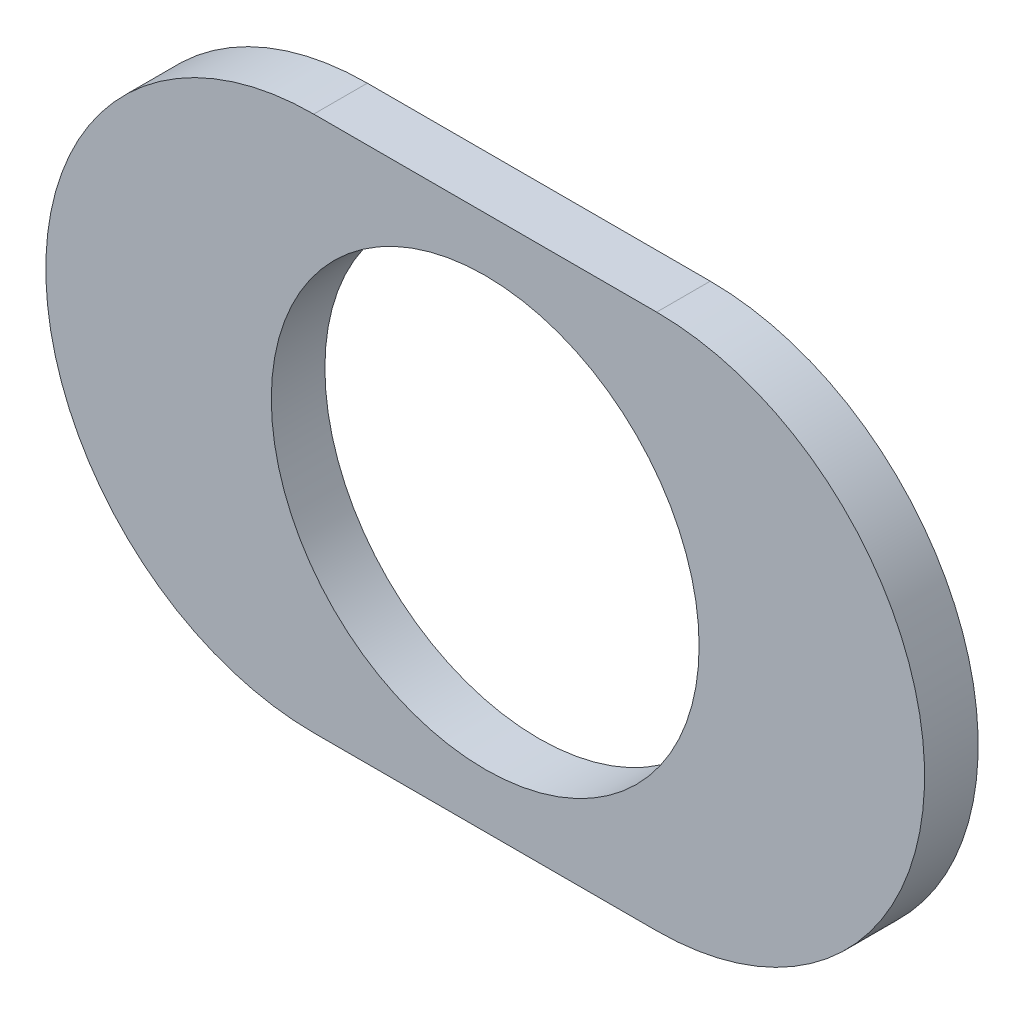
SolidWorks part; units mm, degrees
material "Delrin 2700 NC010, Low Viscosity Acetal Copolymer (SS)"
ref_plane "Front Plane" through (0, 0, 0) normal (0, 0, 1) x (1, 0, 0)
ref_plane "Top Plane" through (0, 0, 0) normal (0, 1, 0) x (1, 0, 0)
ref_plane "Right Plane" through (0, 0, 0) normal (1, 0, 0) x (0, 0, -1)
sketch "Sketch1" plane through (0, 0, 0) normal (0, 0, 1) x (1, 0, 0)
  line L0 (5.08, 0) -> (-5.08, 0) construction
  line L1 (5.08, -7.9375) -> (-5.08, -7.9375)
  line L2 (5.08, 7.9375) -> (-5.08, 7.9375)
  arc A0 (5.08, -7.9375) -> (5.08, 7.9375) centre (5.08, 0) ccw
  arc A1 (-5.08, 7.9375) -> (-5.08, -7.9375) centre (-5.08, 0) ccw
  circle A2 centre (0, 0) radius 6.3373
  point P2 (0, 0)
  dimension "D1" = 7.9375
  dimension "D3" = 12.6746
  dimension "D2" = 10.16
extrude "Boss-Extrude1" add sketch "Sketch1" along normal mid plane 1.5875
